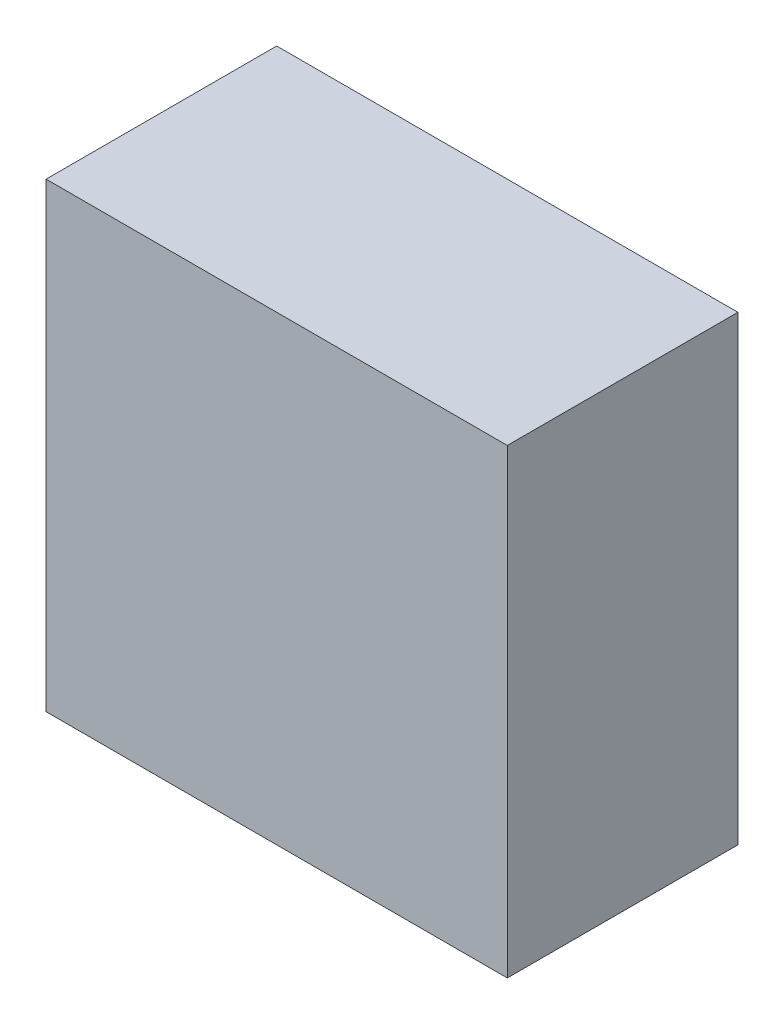
SolidWorks part; units mm, degrees
ref_plane "Front Plane" through (0, 0, 0) normal (0, 0, 1) x (1, 0, 0)
ref_plane "Top Plane" through (0, 0, 0) normal (0, 1, 0) x (1, 0, 0)
ref_plane "Right Plane" through (0, 0, 0) normal (1, 0, 0) x (0, 0, -1)
sketch "Sketch1" plane through (0, 0, 0) normal (0, 0, 1) x (1, 0, 0)
  line L1 (-50, 50) -> (50, 50)
  line L2 (-50, 50) -> (-50, -50)
  line L3 (-50, -50) -> (50, -50)
  line L4 (50, 50) -> (50, -50)
  line L5 (-50, 50) -> (50, -50) construction
  line L6 (-50, -50) -> (50, 50) construction
  point P0 (0, 0)
  dimension "D1" = 100
extrude "Boss-Extrude1" add sketch "Sketch1" along normal mid plane 50
